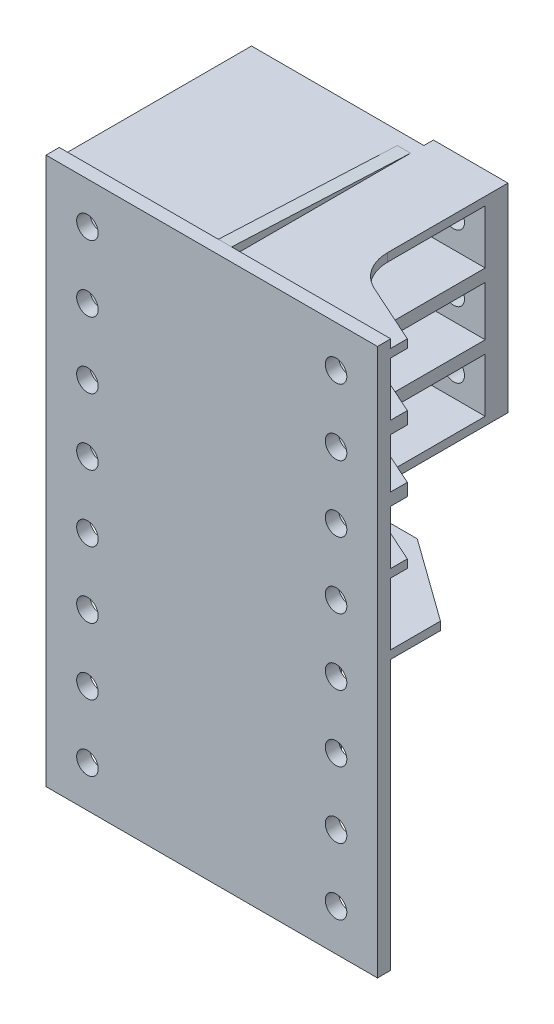
SolidWorks part; units mm, degrees
ref_plane "前视基准面" through (0, 0, 0) normal (0, 0, 1) x (1, 0, 0)
ref_plane "上视基准面" through (0, 0, 0) normal (0, 1, 0) x (1, 0, 0)
ref_plane "右视基准面" through (0, 0, 0) normal (1, 0, 0) x (0, 0, -1)
sketch "草图1" plane through (0, 0, 0) normal (0, 0, 1) x (1, 0, 0)
  line L1 (0, 0) -> (400, 0)
  line L2 (0, 0) -> (0, 660)
  line L3 (0, 660) -> (400, 660)
  line L4 (400, 0) -> (400, 660)
  dimension "D1" = 400
  dimension "D2" = 660
extrude "凸台-拉伸1" add sketch "草图1" along normal blind 16
sketch "草图2" plane through (0, 0, 16) normal (0, 0, 1) x (1, 0, 0)
  line L0 (0, 660) -> (0, 0) construction
  line L1 (400, 660) -> (0, 660) construction
  circle A0 centre (50, 610) radius 13
  dimension "D1" = 26
  dimension "D2" = 50
  dimension "D3" = 50
extrude "切除-拉伸1" cut sketch "草图2" against normal through all
pattern_linear "阵列(线性)1" count 2 spacing 300 along (1, 0, 0) count 8 spacing 80 along (0, -1, 0) of "切除-拉伸1"
sketch "草图3" plane through (0, 0, 16) normal (0, 0, 1) x (1, 0, 0)
  line L0 (200, -340) -> (200, 49660) construction
  line L1 (400, 660) -> (0, 660) construction
  line L2 (0, 0) -> (400, 0) construction
  line L3 (192, 660) -> (208, 660)
  line L4 (192, 660) -> (192, 0)
  line L5 (192, 0) -> (208, 0)
  line L6 (208, 660) -> (208, 0)
  point P5 (200, 660)
  dimension "D1" = 16
extrude "凸台-拉伸2" add sketch "草图3" along normal blind 216
sketch "草图4" plane through (208, 0, 0) normal (1, 0, 0) x (0, 0, -1)
  line L0 (-232, 660) -> (-232, 650)
  line L1 (-232, 0) -> (-232, 660) construction
  line L2 (-232, 650) -> (-16, 660)
  line L3 (-16, 660) -> (-232, 660)
  line L4 (-232, 410) -> (-198.5, 410)
  line L5 (-148.5, 360) -> (-148.5, 0)
  line L6 (-232, 0) -> (-16, 0) construction
  line L7 (-16, 0) -> (-16, 660) construction
  line L8 (-232, 410) -> (-232, 0)
  line L9 (-232, 0) -> (-148.5, 0)
  line L10 (-93.5, -837.4401) -> (-93.5, 49162.5599) construction
  arc A0 (-198.5, 410) -> (-148.5, 360) centre (-198.5, 360) cw
  circle A1 centre (-93.5, 50) radius 13
  circle A2 centre (-93.5, 130) radius 13
  circle A3 centre (-93.5, 210) radius 13
  dimension "D3" = 50
  dimension "D6" = 26
  dimension "D1" = 10
  dimension "D2" = 240
  dimension "D4" = 132.5
  dimension "D5" = 138.5
  dimension "D7" = 50
  dimension "D8" = 80
  dimension "D9" = 80
extrude "切除-拉伸2" cut sketch "草图4" against normal through all
sketch "草图5" plane through (0, 0, 16) normal (0, 0, 1) x (1, 0, 0)
  line L0 (208, 410) -> (208, 650) construction
  line L1 (208, 650) -> (400, 650)
  line L2 (208, 650) -> (208, 640)
  line L3 (208, 640) -> (400, 640)
  line L4 (400, 650) -> (400, 640)
  line L5 (400, 0) -> (400, 660) construction
  line L6 (0, 660) -> (0, 0) construction
  line L7 (0, 650) -> (192, 650)
  line L8 (0, 650) -> (0, 640)
  line L9 (0, 640) -> (192, 640)
  line L10 (192, 650) -> (192, 640)
  line L11 (192, 660) -> (192, 0) construction
  line L12 (400, 660) -> (208, 660) construction
  dimension "D1" = 10
  dimension "D2" = 10
extrude "凸台-拉伸3" add sketch "草图5" along normal blind 216
sketch "草图6" plane through (0, 640, 0) normal (0, -1, 0) x (1, 0, 0)
  line L0 (298, 232) -> (298, 114.3004)
  line L1 (208, 232) -> (400, 232) construction
  line L2 (327.4446, 68.7211) -> (400, 36)
  line L3 (400, 232) -> (400, 16) construction
  line L4 (400, 36) -> (400, 232)
  line L5 (400, 232) -> (298, 232)
  line L6 (208, 198.5) -> (208, 232) construction
  line L7 (208, 16) -> (400, 16) construction
  arc A0 (327.4446, 68.7211) -> (298, 114.3004) centre (348, 114.3004) cw
  point P15 (298, 82)
  dimension "D4" = 50
  dimension "D1" = 90
  dimension "D2" = 66
  dimension "D3" = 20
extrude "切除-拉伸3" cut sketch "草图6" against normal through all
pattern_linear "阵列(线性)2" count 2 spacing 75 along (0, -1, 0) of "凸台-拉伸3", "切除-拉伸3"
pattern_linear "阵列(线性)3" count 2 spacing 80 along (0, -1, 0) of "阵列(线性)2", "凸台-拉伸3"
pattern_linear "阵列(线性)4" count 2 spacing 75 along (0, -1, 0) of "阵列(线性)3", "凸台-拉伸3", "阵列(线性)2"
sketch "草图7" plane through (0, 0, 16) normal (0, 0, 1) x (1, 0, 0)
  line L0 (0, 410) -> (0, 0) construction
  line L1 (0, 335) -> (400, 335)
  line L2 (0, 335) -> (0, 325)
  line L3 (0, 325) -> (400, 325)
  line L4 (400, 335) -> (400, 325)
  line L5 (400, 0) -> (400, 410) construction
  line L6 (298, 410) -> (0, 410) construction
  dimension "D1" = 10
  dimension "D2" = 85
extrude "凸台-拉伸4" add sketch "草图7" along normal blind 132
sketch "草图8" plane through (0, 325, 0) normal (0, -1, 0) x (-1, 0, 0)
  line L0 (-400, -148) -> (-300, -148)
  line L1 (-208, -148) -> (-400, -148) construction
  line L2 (-300, -148) -> (-400, -76)
  line L3 (-400, -148) -> (-400, -16) construction
  line L4 (-400, -76) -> (-400, -148)
  line L5 (0, -148) -> (-100, -148)
  line L6 (0, -148) -> (-192, -148) construction
  line L7 (-100, -148) -> (0, -76)
  line L8 (0, -148) -> (0, -16) construction
  line L9 (0, -76) -> (0, -148)
  line L10 (-208, -16) -> (-400, -16) construction
  dimension "D1" = 60
  dimension "D2" = 100
extrude "切除-拉伸4" cut sketch "草图8" against normal blind 10
sketch "草图9" plane through (0, 0, 232) normal (0, 0, 1) x (1, 0, 0)
  line L1 (0, 650) -> (298, 650)
  line L2 (0, 650) -> (0, 410)
  line L3 (0, 410) -> (298, 410)
  line L4 (298, 650) -> (298, 410)
  line L9 (192, 650) -> (0, 650) construction
  line L10 (298, 410) -> (0, 410) construction
  line L11 (298, 500) -> (298, 485) construction
  line L12 (0, 575) -> (0, 560) construction
extrude "凸台-拉伸5" add sketch "草图9" along normal blind 16
sketch "草图10" plane through (0, 0, 232) normal (0, 0, -1) x (-1, 0, 0)
  line L0 (-200, -640) -> (-200, 49360) construction
  line L1 (-192, 360) -> (-208, 360) construction
  line L2 (-1298, 530) -> (48702, 530) construction
  line L3 (-298, 410) -> (-298, 650) construction
  circle A2 centre (-140, 450) radius 13
  point P7 (-298, 530)
  point P17 (-200, 360)
  dimension "D1" = 26
  dimension "D2" = 60
  dimension "D3" = 80
extrude "切除-拉伸5" cut sketch "草图10" against normal through all
pattern_linear "阵列(线性)6" count 3 spacing 80 along (0, 1, 0) of "切除-拉伸5"
pattern_linear "阵列(线性)7" count 2 spacing 120 along (1, 0, 0) of "阵列(线性)6", "切除-拉伸5"
pattern_linear "阵列(线性)8" count 2 spacing 80 along (-1, 0, 0) of "切除-拉伸5", "阵列(线性)6"
sketch "草图13" plane through (0, 0, 248) normal (0, 0, 1) x (1, 0, 0)
  line L0 (298, 650) -> (0, 650) construction
  line L1 (208, 650) -> (298, 650)
  line L2 (208, 650) -> (208, 410)
  line L3 (208, 410) -> (298, 410)
  line L4 (298, 650) -> (298, 410)
  line L5 (208, 360) -> (208, 410) construction
  circle A0 centre (260, 610) radius 13
  circle A1 centre (260, 530) radius 13
  circle A2 centre (260, 450) radius 13
  circle A3 centre (260, 450) radius 13 construction
  circle A4 centre (260, 530) radius 13 construction
  circle A5 centre (260, 610) radius 13 construction
extrude "凸台-拉伸6" add sketch "草图13" along normal blind 11.5
mirror "镜向1" about plane through (0, 0, 0) normal (0, 0, 1) of bodies 129 126
sketch "草图12" plane through (0, 0, 0) normal (-1, 0, 0) x (0, 0, 1)
  line L1 (0, 0) -> (259.5, 0)
  line L2 (0, 0) -> (0, 660)
  line L3 (0, 660) -> (259.5, 660)
  line L4 (259.5, 0) -> (259.5, 660)
  line L5 (16, 660) -> (-16, 660) construction
  line L6 (259.5, 650) -> (259.5, 410) construction
extrude "切除-拉伸6" cut sketch "草图12" against normal through all
